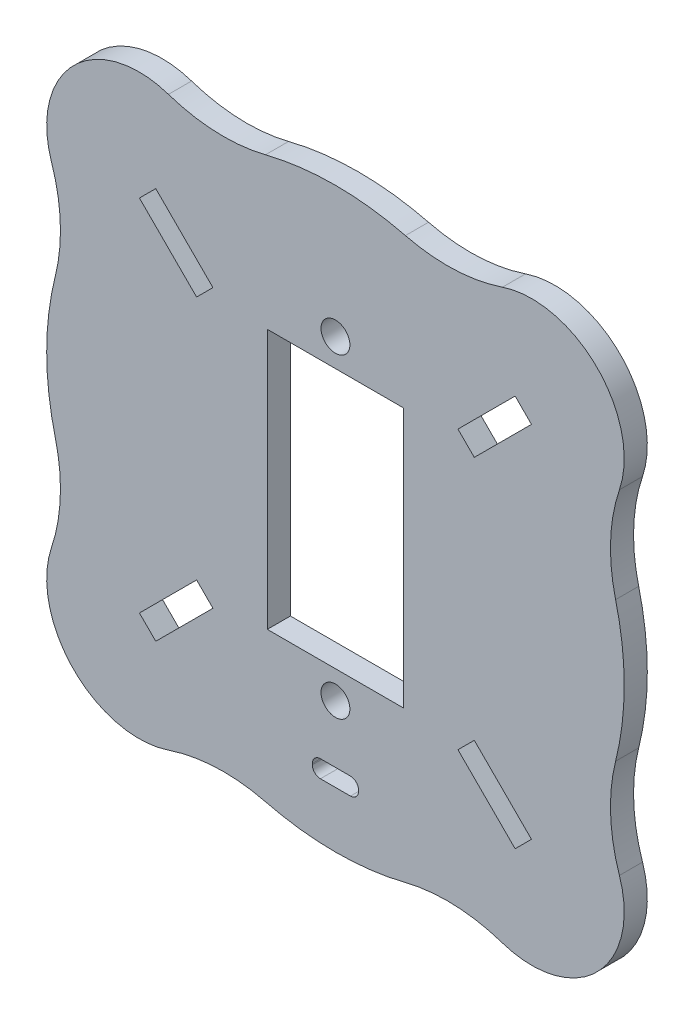
SolidWorks part; units mm, degrees
ref_plane "Front Plane" through (0, 0, 0) normal (0, 0, 1) x (1, 0, 0)
ref_plane "Top Plane" through (0, 0, 0) normal (0, 1, 0) x (1, 0, 0)
ref_plane "Right Plane" through (0, 0, 0) normal (1, 0, 0) x (0, 0, -1)
sketch "Sketch1" plane through (0, 0, 0) normal (0, 0, 1) x (1, 0, 0)
  line L0 (0, 25) -> (17, 25) construction
  line L1 (0, -18.65) -> (0, -13.65) construction
  line L2 (1.3, -18.65) -> (-1.3, -18.65)
  line L3 (2, -19.35) -> (2, -19.45)
  line L4 (1.3, -20.15) -> (-1.3, -20.15)
  line L5 (-2, -19.35) -> (-2, -19.45)
  line L20 (0, 0) -> (0, 24) construction
  line L21 (0, 0) -> (12.0208, 0) construction
  line L22 (-5.9, 11.25) -> (5.9, 11.25)
  line L23 (5.9, 11.25) -> (5.9, -11.25)
  line L24 (-12.0208, 10.6066) -> (-10.6066, 12.0208)
  line L27 (0, 0) -> (34, 34) construction
  line L28 (10.6066, 12.0208) -> (15.5563, 16.9706)
  line L29 (15.5563, 16.9706) -> (16.9706, 15.5563)
  line L30 (16.9706, 15.5563) -> (12.0208, 10.6066)
  line L31 (12.0208, 10.6066) -> (10.6066, 12.0208)
  line L32 (-15.5563, 16.9706) -> (-16.9706, 15.5563)
  line L33 (-10.6066, 12.0208) -> (-15.5563, 16.9706)
  line L34 (-16.9706, 15.5563) -> (-12.0208, 10.6066)
  line L36 (-5.9, 11.25) -> (-5.9, -11.25)
  line L37 (12.0208, -10.6066) -> (10.6066, -12.0208)
  line L38 (15.5563, -16.9706) -> (16.9706, -15.5563)
  line L39 (10.6066, -12.0208) -> (15.5563, -16.9706)
  line L40 (16.9706, -15.5563) -> (12.0208, -10.6066)
  line L41 (-5.9, -11.25) -> (5.9, -11.25)
  line L42 (-16.9706, -15.5563) -> (-12.0208, -10.6066)
  line L43 (-10.6066, -12.0208) -> (-15.5563, -16.9706)
  line L44 (-15.5563, -16.9706) -> (-16.9706, -15.5563)
  line L45 (-12.0208, -10.6066) -> (-10.6066, -12.0208)
  arc A0 (6.0575, 24.255) -> (-6.0575, 24.255) centre (0, 0) ccw
  arc A1 (24.255, 6.0575) -> (24.5854, 14.4581) centre (38.8081, 9.6919) cw
  arc A2 (24.255, 6.0575) -> (24.255, -6.0575) centre (0, 0) cw
  arc A3 (-6.0575, 24.255) -> (-14.4581, 24.5854) centre (-9.6919, 38.8081) cw
  arc A4 (6.0575, 24.255) -> (14.4581, 24.5854) centre (9.6919, 38.8081) ccw
  arc A5 (14.4581, 24.5854) -> (24.5854, 14.4581) centre (17, 17) cw
  arc A6 (-14.4581, 24.5854) -> (-24.5854, 14.4581) centre (-17, 17) ccw
  arc A7 (-24.255, 6.0575) -> (-24.255, -6.0575) centre (0, 0) ccw
  arc A8 (-24.255, 6.0575) -> (-24.5854, 14.4581) centre (-38.8081, 9.6919) ccw
  arc A9 (6.0575, -24.255) -> (14.4581, -24.5854) centre (9.6919, -38.8081) cw
  arc A10 (14.4581, -24.5854) -> (24.5854, -14.4581) centre (17, -17) ccw
  arc A11 (24.255, -6.0575) -> (24.5854, -14.4581) centre (38.8081, -9.6919) ccw
  arc A12 (-6.0575, -24.255) -> (-14.4581, -24.5854) centre (-9.6919, -38.8081) ccw
  arc A13 (6.0575, -24.255) -> (-6.0575, -24.255) centre (0, 0) cw
  arc A14 (-24.255, -6.0575) -> (-24.5854, -14.4581) centre (-38.8081, -9.6919) cw
  arc A15 (-14.4581, -24.5854) -> (-24.5854, -14.4581) centre (-17, -17) cw
  arc A16 (2, -19.45) -> (1.3, -20.15) centre (1.3, -19.45) cw
  arc A17 (1.3, -18.65) -> (2, -19.35) centre (1.3, -19.35) cw
  circle A18 centre (0, 13.65) radius 1.25
  circle A19 centre (0, -13.65) radius 1.25
  arc A20 (-1.3, -18.65) -> (-2, -19.35) centre (-1.3, -19.35) ccw
  arc A21 (-1.3, -20.15) -> (-2, -19.45) centre (-1.3, -19.45) cw
  point P37 (2, -20.15)
  point P40 (2, -18.65)
  point P43 (-2, -18.65)
  point P76 (0, 11.25)
  point P84 (5.9, 0)
  point P85 (-5.9, 0)
  dimension "D16" = 2.5
  dimension "D3" = 15
  dimension "D4" = 25
  dimension "D5" = 8
  dimension "D15" = 0.7
  dimension "D2" = 45
  dimension "D6" = 1.5
  dimension "D7" = 5.9
  dimension "D8" = 11.25
  dimension "D9" = 4
  dimension "D10" = 7
  dimension "D11" = 1
  dimension "D12" = 2
  dimension "D13" = 16
  dimension "D14" = 5
  dimension "D17" = 2.4
extrude "Boss-Extrude1" add sketch "Sketch1" along normal blind 2
